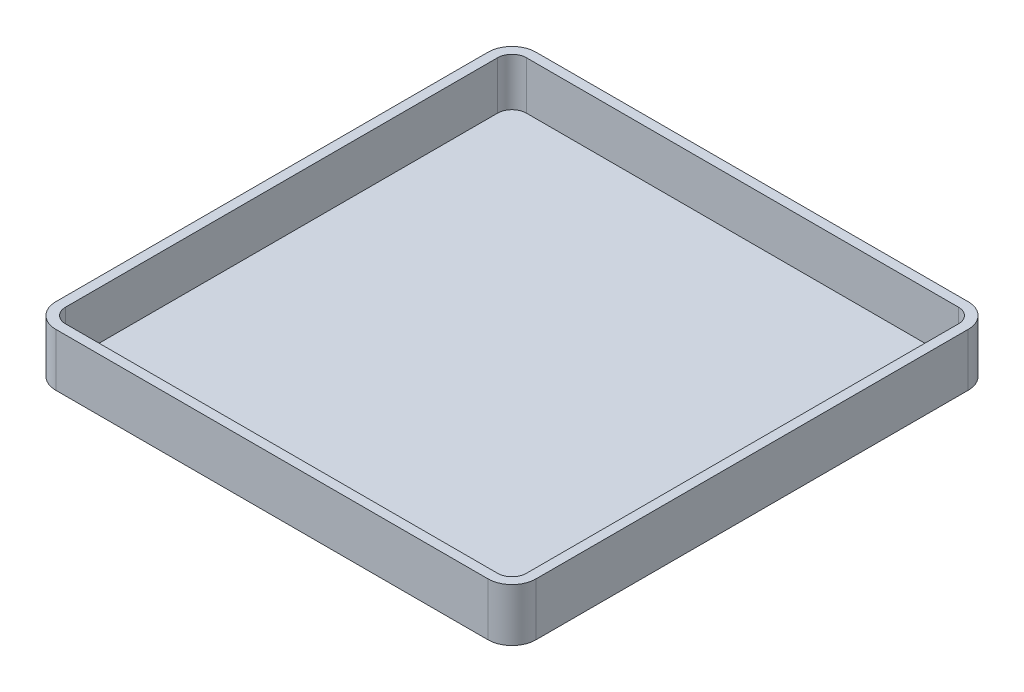
SolidWorks part; units mm, degrees
ref_plane "Front Plane" through (0, 0, 0) normal (0, 0, 1) x (1, 0, 0)
ref_plane "Top Plane" through (0, 0, 0) normal (0, 1, 0) x (1, 0, 0)
ref_plane "Right Plane" through (0, 0, 0) normal (1, 0, 0) x (0, 0, -1)
sketch "Sketch1" plane through (0, 0, 0) normal (0, 1, 0) x (1, 0, 0)
  line L1 (-50, 50) -> (50, 50)
  line L2 (-50, 50) -> (-50, -50)
  line L3 (-50, -50) -> (50, -50)
  line L4 (50, 50) -> (50, -50)
  line L5 (-50, 50) -> (50, -50) construction
  line L6 (-50, -50) -> (50, 50) construction
  point P0 (0, 0)
  dimension "D1" = 100
extrude "Extrude-Thin1" add sketch "Sketch1" along normal blind 10 thin
fillet "Fillet1" radius 5 4 edges at (-50, 5, 50) (-50, 5, -50) (50, 5, -50) (50, 5, 50)
fillet "Fillet2" radius 3 4 edges at (-48, 5, 48) (48, 5, 48) (48, 5, -48) (-48, 5, -48)
sketch "Sketch2" plane through (0, 0, 0) normal (0, -1, 0) x (1, 0, 0)
  line L4 (45, 50) -> (-45, 50)
  line L5 (-50, 45) -> (-50, -45)
  line L6 (-45, -50) -> (45, -50)
  line L7 (50, -45) -> (50, 45)
  line L8 (45, 50) -> (-45, 50)
  line L9 (-50, 45) -> (-50, -45)
  line L10 (-45, -50) -> (45, -50)
  line L11 (50, -45) -> (50, 45)
  arc A4 (-45, 50) -> (-50, 45) centre (-45, 45) ccw
  arc A5 (-50, -45) -> (-45, -50) centre (-45, -45) ccw
  arc A6 (45, -50) -> (50, -45) centre (45, -45) ccw
  arc A7 (50, 45) -> (45, 50) centre (45, 45) ccw
  arc A8 (-45, 50) -> (-50, 45) centre (-45, 45) ccw
  arc A9 (-50, -45) -> (-45, -50) centre (-45, -45) ccw
  arc A10 (45, -50) -> (50, -45) centre (45, -45) ccw
  arc A11 (50, 45) -> (45, 50) centre (45, 45) ccw
  dimension "D1" = 0
extrude "Boss-Extrude1" add sketch "Sketch2" along normal blind 1
